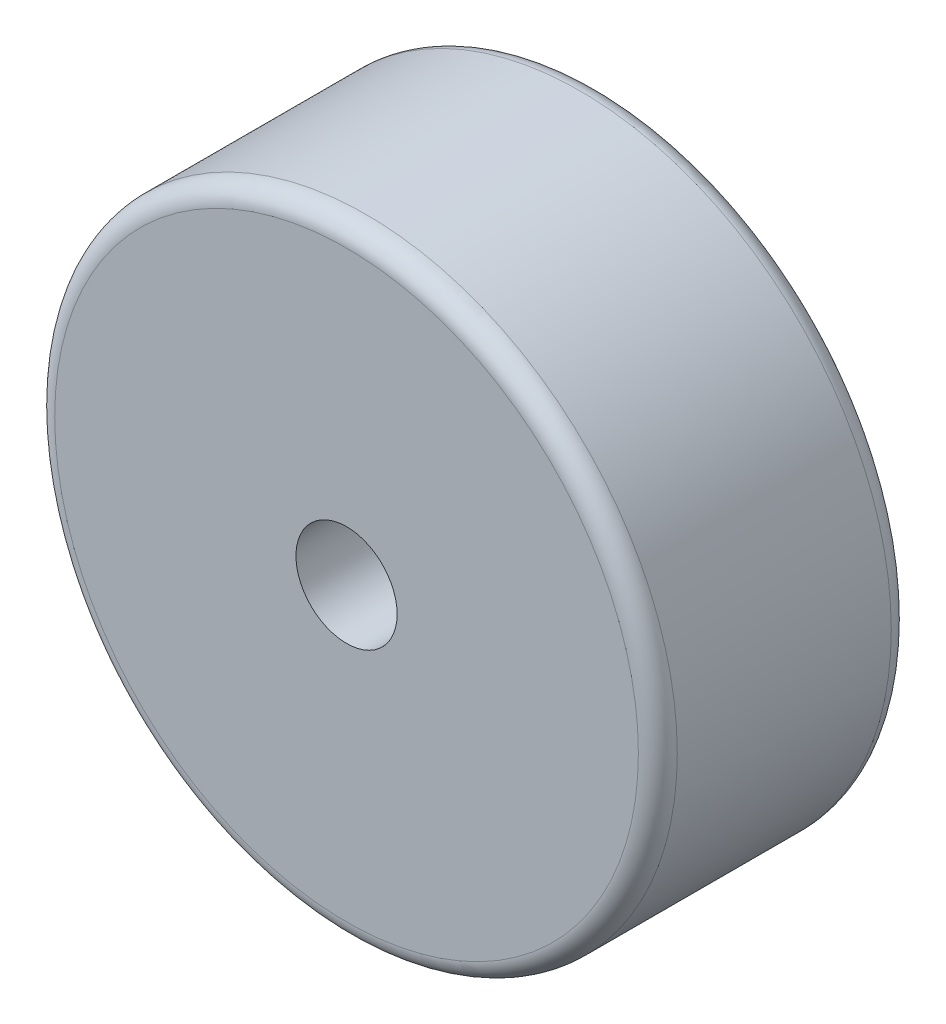
SolidWorks part; units mm, degrees
ref_plane "前视基准面" through (0, 0, 0) normal (0, 0, 1) x (1, 0, 0)
ref_plane "上视基准面" through (0, 0, 0) normal (0, 1, 0) x (1, 0, 0)
ref_plane "右视基准面" through (0, 0, 0) normal (1, 0, 0) x (0, 0, -1)
other "Configuration Table"
sketch "草图1" plane through (0, 0, 0) normal (0, 0, 1) x (1, 0, 0)
  circle A0 centre (0, 0) radius 16
  dimension "D1" = 32
extrude "凸台-拉伸1" add sketch "草图1" along normal blind 13
sketch "草图2" plane through (0, 0, 13) normal (0, 0, 1) x (1, 0, 0)
  circle A0 centre (0, 0) radius 2.6
  dimension "D1" = 5.2
extrude "切除-拉伸1" cut sketch "草图2" against normal through all
fillet "圆角1" radius 1 2 edges at (16, 0, 0) (16, 0, 13)
